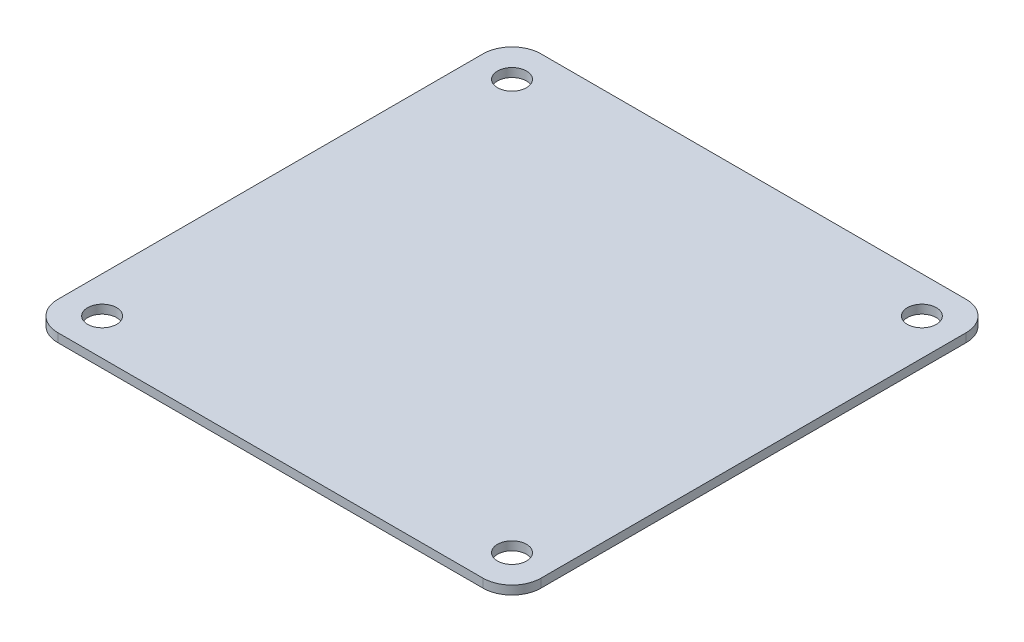
SolidWorks part; units mm, degrees
ref_plane "Front Plane" through (0, 0, 0) normal (0, 0, 1) x (1, 0, 0)
ref_plane "Top Plane" through (0, 0, 0) normal (0, 1, 0) x (1, 0, 0)
ref_plane "Right Plane" through (0, 0, 0) normal (1, 0, 0) x (0, 0, -1)
sketch "Sketch2" plane through (0, 0, 0) normal (0, 1, 0) x (1, 0, 0)
  line L1 (-50, 50) -> (50, 50)
  line L2 (-50, 50) -> (-50, -50)
  line L3 (-50, -50) -> (50, -50)
  line L4 (50, 50) -> (50, -50)
  circle A0 centre (-42.425, 42.425) radius 3
  circle A1 centre (42.425, 42.425) radius 3
  circle A2 centre (42.425, -42.425) radius 3
  circle A3 centre (-42.425, -42.425) radius 3
  point P0 (0, 0)
  point P6 (0, 0)
  point P8 (-42.5754, 42.5754)
  point P15 (42.5754, 42.5754)
  point P23 (-42.5754, -42.5754)
  point P31 (42.5754, -42.5754)
  dimension "D5" = 6
  dimension "D1" = 100
  dimension "D2" = 100
  dimension "D3" = 84.85
  dimension "D4" = 84.85
extrude "Boss-Extrude1" add sketch "Sketch2" along normal blind 1.8
fillet "Fillet1" radius 6 4 edges at (-50, 0.9, 50) (-50, 0.9, -50) (50, 0.9, -50) (50, 0.9, 50)
sketch "Sketch3" plane through (0, 0, 0) normal (0, -1, 0) x (1, 0, 0)
  circle A0 centre (0, 0) radius 42
  circle A1 centre (0, 0) radius 40
  dimension "D1" = 80
  dimension "D2" = 84
extrude "Boss-Extrude2" add sketch "Sketch3" along normal blind 3
